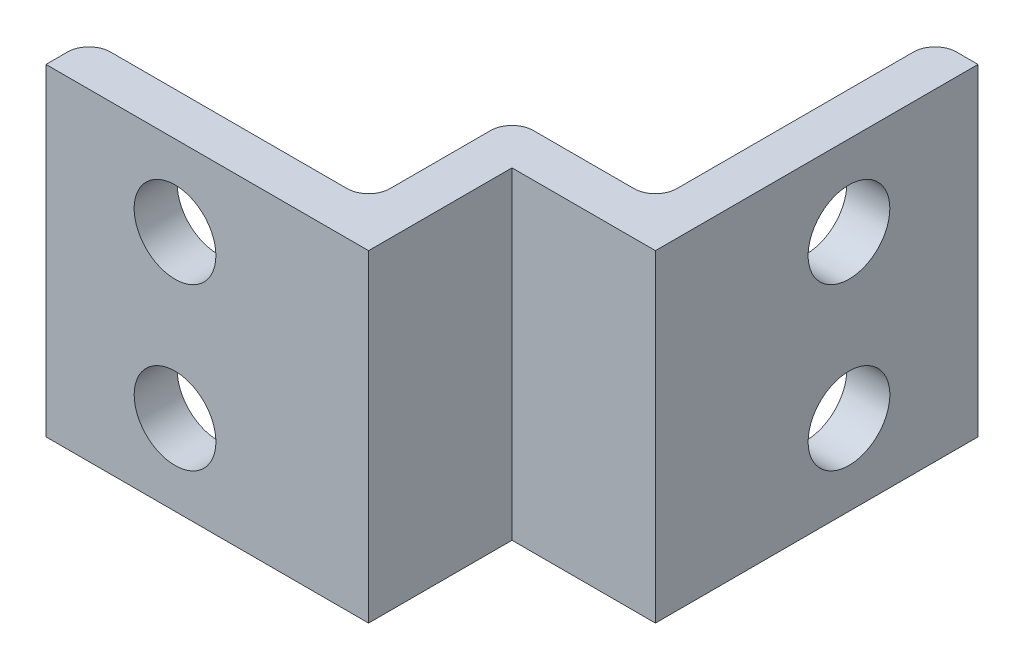
SolidWorks part; units mm, degrees
ref_plane "Front Plane" through (0, 0, 0) normal (0, 0, 1) x (1, 0, 0)
ref_plane "Top Plane" through (0, 0, 0) normal (0, 1, 0) x (1, 0, 0)
ref_plane "Right Plane" through (0, 0, 0) normal (1, 0, 0) x (0, 0, -1)
sketch "Sketch2" plane through (0, 0, 0) normal (0, 0, 1) x (1, 0, 0)
  line L5 (0, 0) -> (38.1, 0)
  line L6 (0, 0) -> (0, 38.1)
  line L7 (0, 38.1) -> (38.1, 38.1)
  line L8 (38.1, 0) -> (38.1, 38.1)
  dimension "D1" = 38.1
  dimension "D2" = 38.1
extrude "Boss-Extrude1" add sketch "Sketch2" against normal blind 5.08
sketch "Sketch3" plane through (38.1, 0, 0) normal (1, 0, 0) x (0, 0, -1)
  line L1 (0, 0) -> (22.0218, 0)
  line L2 (0, 0) -> (0, 38.1)
  line L3 (0, 38.1) -> (22.0218, 38.1)
  line L4 (22.0218, 0) -> (22.0218, 38.1)
  dimension "D1" = 22.0218
  dimension "D2" = 38.1
extrude "Boss-Extrude2" add sketch "Sketch3" against normal blind 5.08
sketch "Sketch4" plane through (0, 0, -22.0218) normal (0, 0, -1) x (-1, 0, 0)
  line L1 (-33.02, 0) -> (-55.0418, 0)
  line L2 (-33.02, 0) -> (-33.02, 38.1)
  line L3 (-33.02, 38.1) -> (-55.0418, 38.1)
  line L4 (-55.0418, 0) -> (-55.0418, 38.1)
  dimension "D1" = 22.0218
  dimension "D2" = 38.1
extrude "Boss-Extrude3" add sketch "Sketch4" against normal blind 5.08
sketch "Sketch5" plane through (55.0418, 0, 0) normal (1, 0, 0) x (0, 0, -1)
  line L1 (16.9418, 0) -> (55.0418, 0)
  line L2 (16.9418, 0) -> (16.9418, 38.1)
  line L3 (16.9418, 38.1) -> (55.0418, 38.1)
  line L4 (55.0418, 0) -> (55.0418, 38.1)
  dimension "D1" = 38.1
  dimension "D2" = 38.1
extrude "Boss-Extrude4" add sketch "Sketch5" against normal blind 5.08
sketch "Sketch6" plane through (55.0418, 0, 0) normal (1, 0, 0) x (0, 0, -1)
  line L0 (26.1686, 19.05) -> (66.714, 19.05) construction
  line L1 (55.0418, 0) -> (55.0418, 38.1) construction
  line L2 (16.9418, 38.1) -> (55.0418, 38.1) construction
  circle A0 centre (39.8018, 28.575) radius 4.826
  circle A1 centre (39.8018, 9.525) radius 4.826
  dimension "D1" = 15.24
  dimension "D3" = 9.652
  dimension "D2" = 9.525
extrude "Cut-Extrude1" cut sketch "Sketch6" against normal through all
sketch "Sketch7" plane through (0, 0, 0) normal (0, 0, 1) x (1, 0, 0)
  line L0 (2.1859, 19.05) -> (39.3525, 19.05) construction
  line L1 (0, 38.1) -> (0, 0) construction
  line L2 (38.1, 38.1) -> (0, 38.1) construction
  circle A0 centre (15.24, 28.575) radius 4.826
  circle A1 centre (15.24, 9.525) radius 4.826
  dimension "D1" = 15.24
  dimension "D3" = 9.652
  dimension "D2" = 9.525
extrude "Cut-Extrude2" cut sketch "Sketch7" against normal through all
fillet "Fillet1" radius 2.54 1 edges at (49.9618, 19.05, -55.0418)
fillet "Fillet2" radius 2.54 1 edges at (49.9618, 19.05, -22.0218)
fillet "Fillet3" radius 2.54 1 edges at (33.02, 19.05, -22.0218)
fillet "Fillet4" radius 2.54 1 edges at (33.02, 19.05, -5.08)
fillet "Fillet5" radius 2.54 1 edges at (0, 19.05, -5.08)
